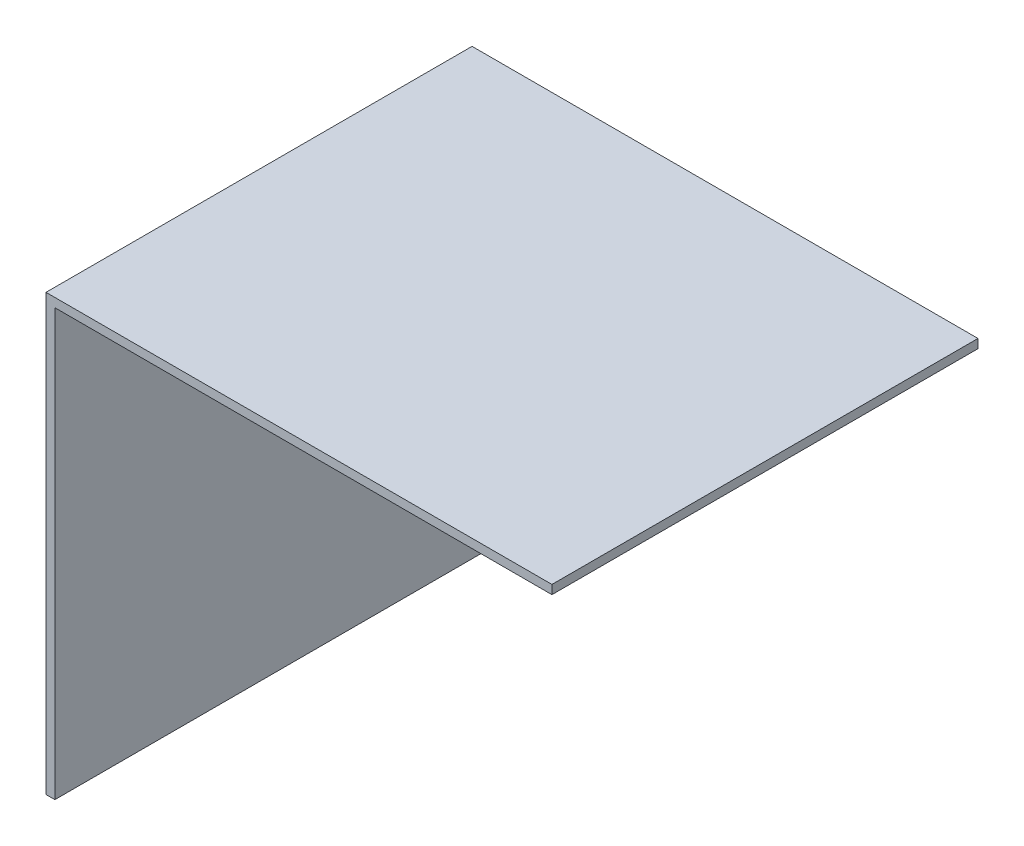
SolidWorks part; units mm, degrees
material "Glass"
ref_plane "Front Plane" through (0, 0, 0) normal (0, 0, 1) x (1, 0, 0)
ref_plane "Top Plane" through (0, 0, 0) normal (0, 1, 0) x (1, 0, 0)
ref_plane "Right Plane" through (0, 0, 0) normal (1, 0, 0) x (0, 0, -1)
sketch "Sketch1" plane through (0, 0, 0) normal (0, 0, 1) x (1, 0, 0)
  line L1 (0, 0) -> (180.975, 0)
  line L2 (0, 0) -> (0, 155.575)
  line L3 (0, 155.575) -> (180.975, 155.575)
  line L4 (180.975, 0) -> (180.975, 155.575)
  line L5 (3.175, 0) -> (180.975, 0)
  line L6 (3.175, 0) -> (3.175, 152.4)
  line L7 (3.175, 152.4) -> (180.975, 152.4)
  line L8 (180.975, 0) -> (180.975, 152.4)
  dimension "D1" = 177.8
  dimension "D2" = 152.4
  dimension "D3" = 0
  dimension "D4" = 0
  dimension "D5" = 3.175
  dimension "D6" = 3.175
extrude "Boss-Extrude1" add sketch "Sketch1" along normal blind 152.4 contours L8 L1 L4 L3 L2 L6 L7
